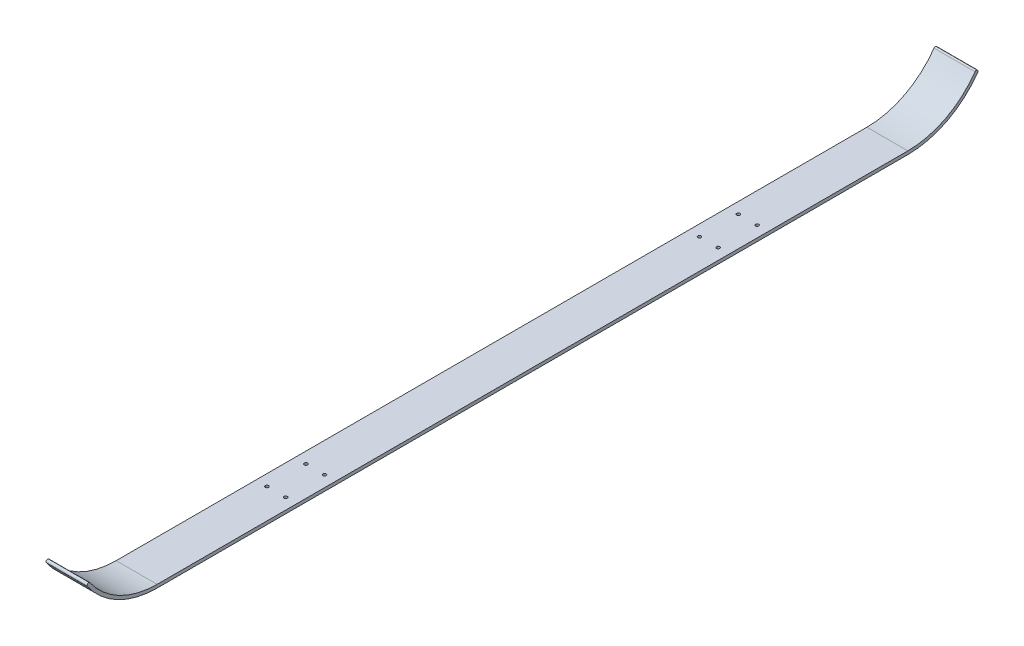
SolidWorks part; units mm, degrees
ref_plane "Front Plane" through (0, 0, 0) normal (0, 0, 1) x (1, 0, 0)
ref_plane "Top Plane" through (0, 0, 0) normal (0, 1, 0) x (1, 0, 0)
ref_plane "Right Plane" through (0, 0, 0) normal (1, 0, 0) x (0, 0, -1)
sketch "Sketch1" plane through (0, 0, 0) normal (0, 1, 0) x (1, 0, 0)
  line L0 (0, 791.5) -> (0, -791.5) construction
  line L1 (-75, -1274) -> (75, -1274)
  line L2 (-75, -1274) -> (-75, 1274)
  line L3 (-75, 1274) -> (75, 1274)
  line L4 (75, -1274) -> (75, 1274)
  line L5 (-75, -1274) -> (75, 1274) construction
  line L6 (-75, 1274) -> (75, -1274) construction
  line L7 (-75, 0) -> (75, 0) construction
  line L8 (-34.25, 720.25) -> (34.25, 720.25) construction
  line L9 (-34.25, 720.25) -> (-34.25, 862.75) construction
  line L10 (-34.25, 862.75) -> (34.25, 862.75) construction
  line L11 (34.25, 720.25) -> (34.25, 862.75) construction
  line L12 (-34.25, 720.25) -> (34.25, 862.75) construction
  line L13 (-34.25, 862.75) -> (34.25, 720.25) construction
  circle A0 centre (-34.25, 720.25) radius 6
  circle A1 centre (34.25, 720.25) radius 6
  circle A2 centre (-34.25, 862.75) radius 6
  circle A3 centre (34.25, 862.75) radius 6
  circle A4 centre (34.25, -720.25) radius 6
  circle A5 centre (-34.25, -720.25) radius 6
  circle A6 centre (34.25, -862.75) radius 6
  circle A7 centre (-34.25, -862.75) radius 6
  point P0 (0, 0)
  dimension "D6" = 12
  dimension "D1" = 150
  dimension "D2" = 2548
  dimension "D3" = 1583
  dimension "D4" = 142.5
  dimension "D5" = 68.5
extrude "Boss-Extrude1" add sketch "Sketch1" along normal blind 12
sketch "Sketch2" plane through (75, 0, 0) normal (1, 0, 0) x (0, 0, -1)
  line L0 (-1274, 0) -> (-1374, 0)
  line L1 (-1274, 0) -> (-1274, 12)
  line L2 (-1274, 12) -> (-1374, 12)
  line L3 (-1619.7456, 139.9271) -> (-1629.5754, 133.0442) construction
  line L4 (-1374, 0) -> (-1374, 312) construction
  line L5 (-1274, 6) -> (1274, 6) construction
  line L6 (1274, 12) -> (1274, 0) construction
  line L7 (0, 0) -> (0, 12) construction
  line L8 (-1274, 12) -> (1274, 12) construction
  line L9 (1274, 12) -> (1374, 12)
  line L10 (1274, 0) -> (1274, 12)
  line L11 (1274, 0) -> (1374, 0)
  arc A0 (-1619.7456, 139.9271) -> (-1374, 12) centre (-1374, 312) ccw
  arc A1 (-1629.5754, 133.0442) -> (-1374, 0) centre (-1374, 312) ccw
  arc A2 (-1619.7456, 139.9271) -> (-1629.5754, 133.0442) centre (-1624.6605, 136.4856) ccw
  arc A3 (1619.7456, 139.9271) -> (1374, 12) centre (1374, 312) cw
  arc A4 (1629.5754, 133.0442) -> (1374, 0) centre (1374, 312) cw
  arc A5 (1619.7456, 139.9271) -> (1629.5754, 133.0442) centre (1624.6605, 136.4856) cw
  dimension "D3" = 300
  dimension "D1" = 100
  dimension "D2" = 55
extrude "Boss-Extrude2" add sketch "Sketch2" along direction (1, 0, 0) on the side against the normal up to surface (150 mm away)
equation "\"mbtOD\" = 850"
equation "\"mbtT\" = 6"
equation "\"mbtL\" = 1500"
equation "\"mbtFlangeOD\" = 950"
equation "\"mbtFlangeT\" = 12"
equation "\"mbtFlangeBoltCircleDia\" = 650"
equation "\"mbtFlangeHoleDia\" = 12"
equation "\"mbtOringSize\" = 10 "
equation "\"mbtOringDia\" = 620"
equation "\"mbtWidth\" = 2250"
equation "\"skiWidth\" = 1250"
equation "\"D2@Sketch1\"=\"mbtL\"+4*\"mbtFlangeT\"+2*\"mbtCapL\""
equation "\"mbtCapL\" = 500"
equation "\"D3@Sketch1\"=\"mbtL\"+4*\"mbtFlangeT\"+35mm"
